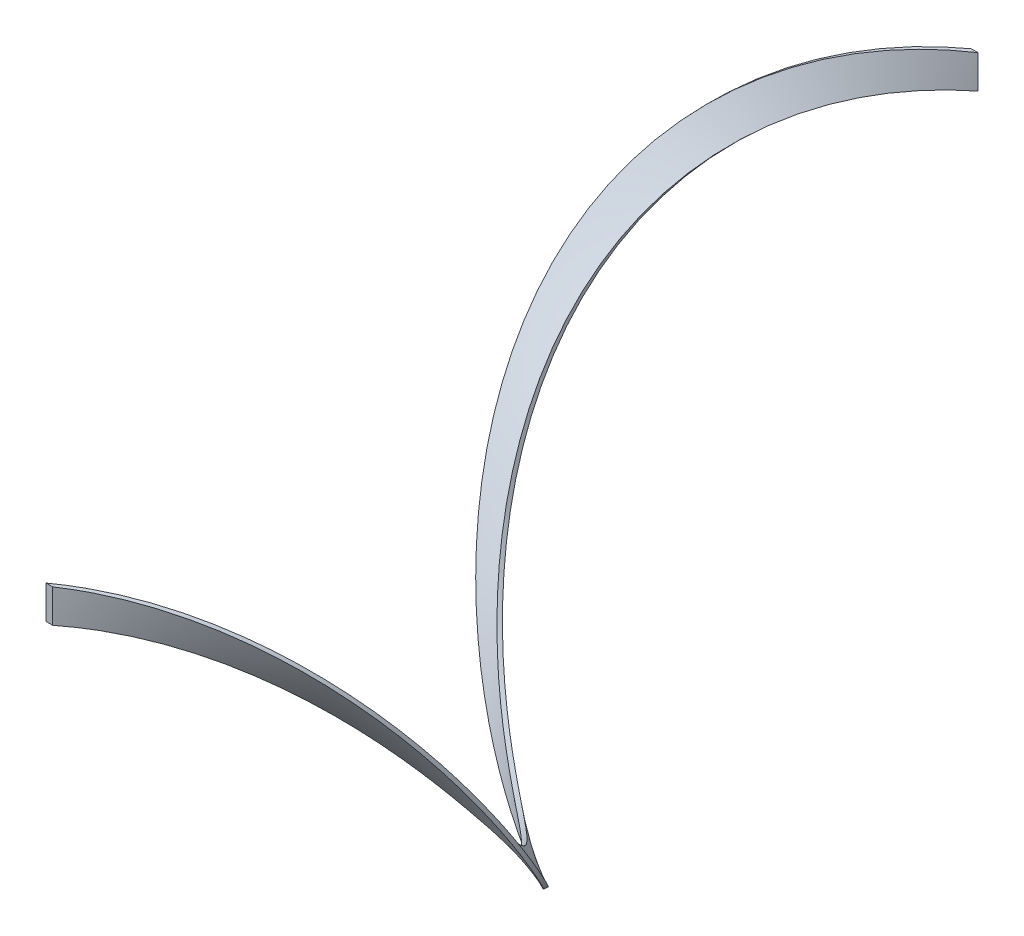
SolidWorks part; units mm, degrees
ref_plane "Front Plane" through (0, 0, 0) normal (0, 0, 1) x (1, 0, 0)
ref_plane "Top Plane" through (0, 0, 0) normal (0, 1, 0) x (1, 0, 0)
ref_plane "Right Plane" through (0, 0, 0) normal (1, 0, 0) x (0, 0, -1)
sketch "Sketch1" plane through (0, 0, 0) normal (0, 0, 1) x (1, 0, 0)
  line L0 (0, -190.5) -> (0, 190.5) construction
  circle A0 centre (0, 0) radius 190.5
  point P6 (0, 0)
  dimension "D1" = 381
curve "Helix/Spiral1" pitch 833 height 833 turns 1
sketch "Sketch2" plane through (0, 0, 0) normal (0, 0, 1) x (1, 0, 0)
  line L1 (-3, 190.4764) -> (3, 190.4764)
  line L2 (-3, 190.4764) -> (-3, 160.4764)
  line L3 (-3, 160.4764) -> (3, 160.4764)
  line L4 (3, 190.4764) -> (3, 160.4764)
  dimension "D1" = 6
  dimension "D2" = 30
sweep "Sweep1" add profiles "Sketch2" path "Helix/Spiral1"
